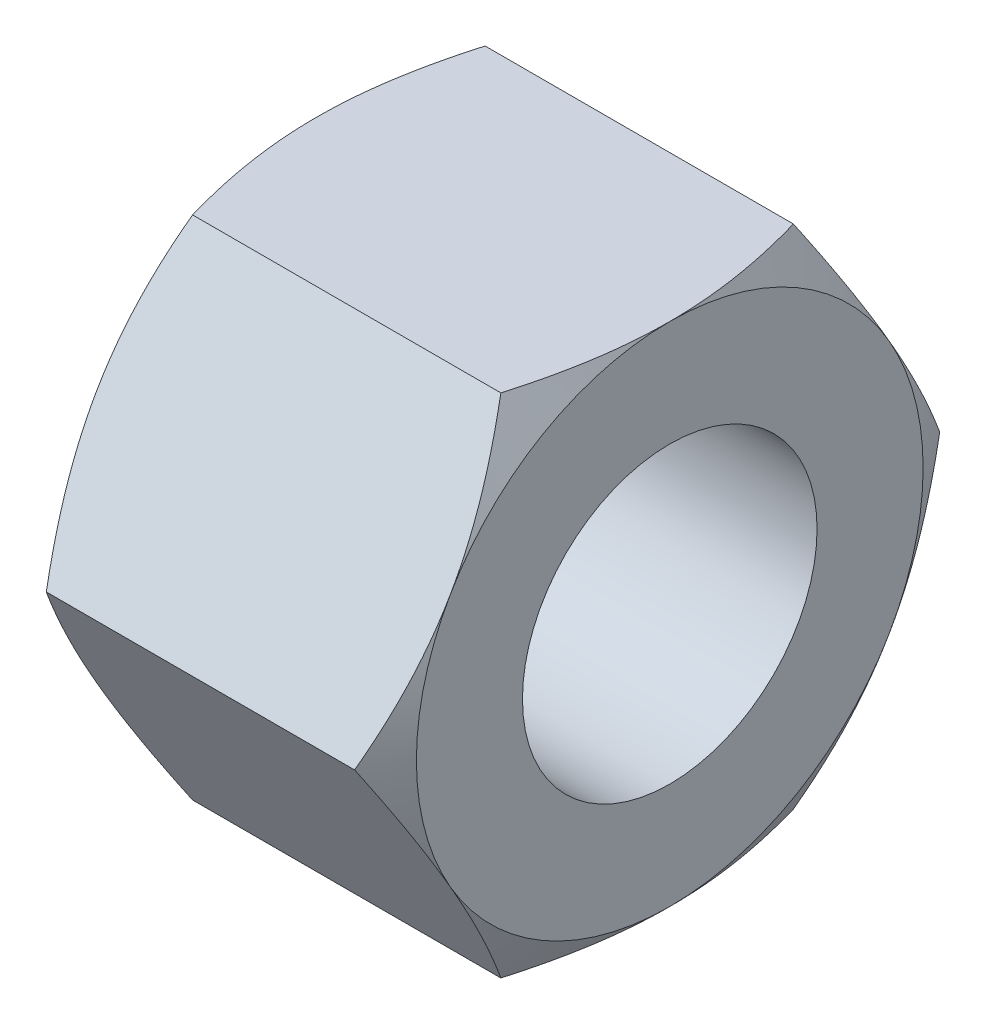
SolidWorks part; units mm, degrees
ref_plane "Ön Düzlem" through (0, 0, 0) normal (0, 0, 1) x (1, 0, 0)
ref_plane "Üst Düzlem" through (0, 0, 0) normal (0, 1, 0) x (1, 0, 0)
ref_plane "Sağ Düzlem" through (0, 0, 0) normal (1, 0, 0) x (0, 0, -1)
sketch "Çizim1" plane through (0, 0, 0) normal (1, 0, 0) x (0, 0, -1)
  line L1 (2.4826, 0) -> (1.2413, 2.15)
  line L2 (1.2413, 2.15) -> (-1.2413, 2.15)
  line L3 (-1.2413, 2.15) -> (-2.4826, 0)
  line L4 (-2.4826, 0) -> (-1.2413, -2.15)
  line L5 (-1.2413, -2.15) -> (1.2413, -2.15)
  line L6 (1.2413, -2.15) -> (2.4826, 0)
  circle A0 centre (0, 0) radius 2.15 construction
  circle A1 centre (0, 0) radius 1.25
  dimension "D2" = 2.5
  dimension "D1" = 4.3
extrude "Yükseklik-Ekstrüzyon1" add sketch "Çizim1" along normal blind 3
sketch "Çizim2" plane through (3, 0, 0) normal (1, 0, 0) x (0, 0, -1)
  circle A0 centre (0, 0) radius 2.15
extrude "Kes-Ekstrüzyon1" cut sketch "Çizim2" against normal blind 10 draft 60 flip side to cut
sketch "Çizim3" plane through (0, 0, 0) normal (-1, 0, 0) x (0, 0, 1)
  circle A0 centre (0, 0) radius 2.15
extrude "Kes-Ekstrüzyon2" cut sketch "Çizim3" against normal blind 10 draft 60 flip side to cut
